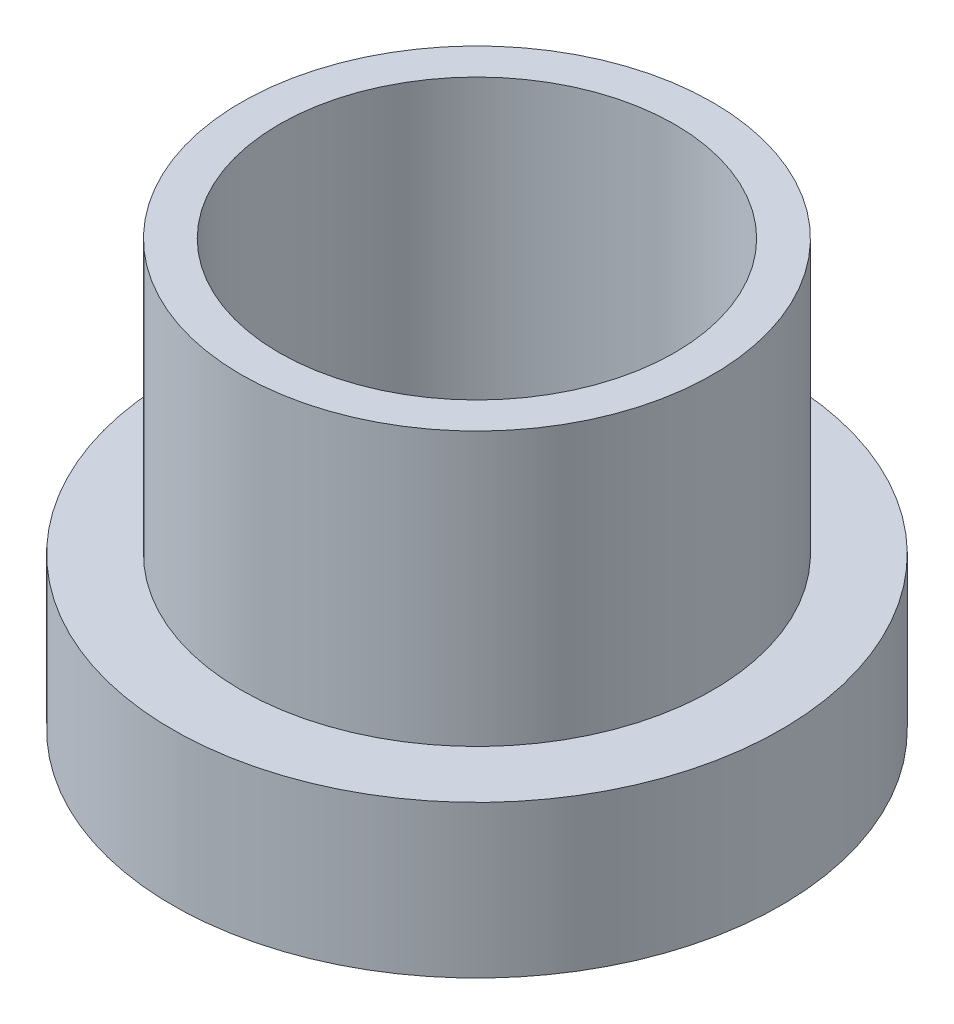
SolidWorks part; units mm, degrees
ref_plane "Front Plane" through (0, 0, 0) normal (0, 0, 1) x (1, 0, 0)
ref_plane "Top Plane" through (0, 0, 0) normal (0, 1, 0) x (1, 0, 0)
ref_plane "Right Plane" through (0, 0, 0) normal (1, 0, 0) x (0, 0, -1)
sketch "Sketch1" plane through (0, 0, 0) normal (0, 1, 0) x (1, 0, 0)
  circle A0 centre (0, 0) radius 2.6
  circle A1 centre (0, 0) radius 3.1
  dimension "D1" = 5.2
  dimension "D2" = 6.2
extrude "Boss-Extrude1" add sketch "Sketch1" along normal blind 5.5909
sketch "Sketch2" plane through (0, 0, 0) normal (0, -1, 0) x (1, 0, 0)
  circle A0 centre (0, 0) radius 2.6
  circle A1 centre (0, 0) radius 4
  dimension "D1" = 8
  dimension "D2" = 5.2
extrude "Boss-Extrude2" add sketch "Sketch2" against normal blind 2
